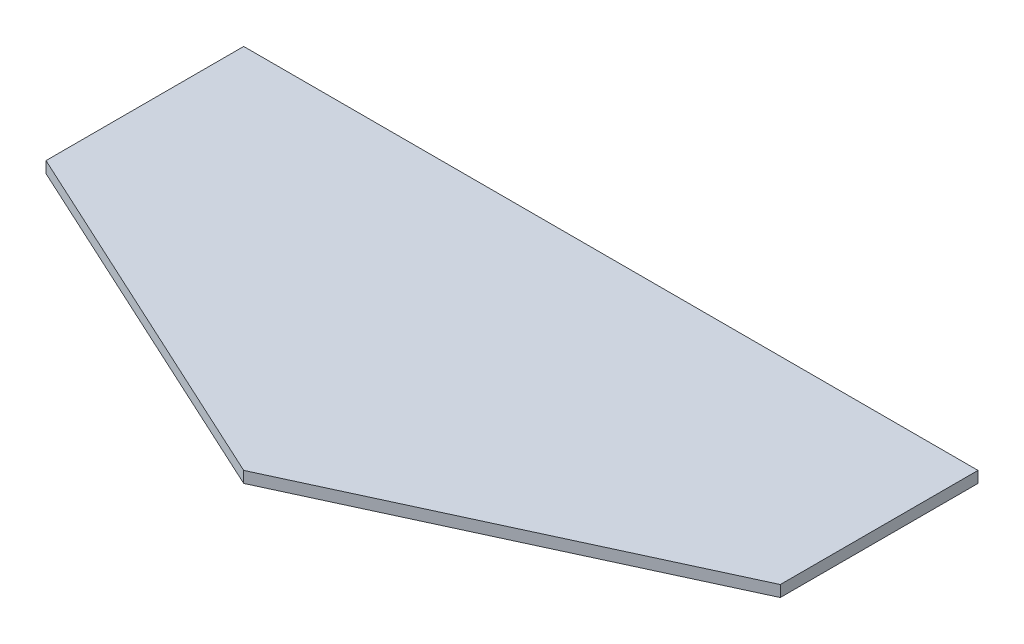
SolidWorks part; units mm, degrees
ref_plane "Front Plane" through (0, 0, 0) normal (0, 0, 1) x (1, 0, 0)
ref_plane "Top Plane" through (0, 0, 0) normal (0, 1, 0) x (1, 0, 0)
ref_plane "Right Plane" through (0, 0, 0) normal (1, 0, 0) x (0, 0, -1)
sketch "Sketch1" plane through (0, 0, 0) normal (0, 1, 0) x (1, 0, 0)
  line L0 (0, -70) -> (130, -130)
  line L1 (0, 0) -> (260, 0)
  line L2 (0, 0) -> (0, -70)
  line L3 (0, -70) -> (260, -70)
  line L4 (260, 0) -> (260, -70)
  line L5 (130, -130) -> (260, -70)
  line L6 (130, -130) -> (130, -70) construction
  dimension "D1" = 260
  dimension "D2" = 70
  dimension "D3" = 60
extrude "Boss-Extrude1" add sketch "Sketch1" along normal blind 4 contours L0 L6 L3 | L4 L1 L2 L3 | L6 L5 L3
ref_plane "Plane1" through (130, 0, 0) normal (1, 0, 0) x (0, 0, -1)
